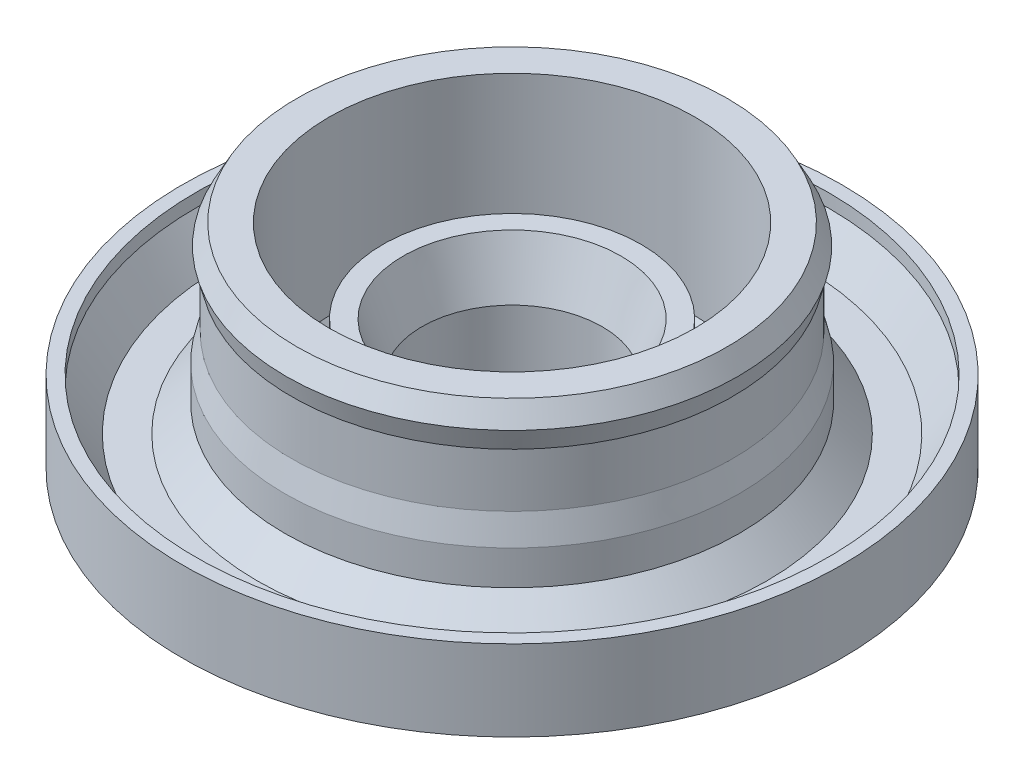
SolidWorks part; units mm, degrees
ref_plane "Front Plane" through (0, 0, 0) normal (0, 0, 1) x (1, 0, 0)
ref_plane "Top Plane" through (0, 0, 0) normal (0, 1, 0) x (1, 0, 0)
ref_plane "Right Plane" through (0, 0, 0) normal (1, 0, 0) x (0, 0, -1)
sketch "Sketch1" plane through (0, 0, 0) normal (0, 0, 1) x (1, 0, 0)
  line L0 (0, 0) -> (0, 11.7229) construction
  line L1 (-12.25, 7.1) -> (-4.45, 7.1)
  line L2 (-4.45, 7.1) -> (-4.45, 0)
  line L3 (-4.45, 0) -> (-6, 0)
  line L4 (-6, 0) -> (-6, 4.1)
  line L5 (-6, 4.1) -> (-12.25, 4.1)
  line L6 (-12.25, 4.1) -> (-12.25, 7.1)
  dimension "D1" = 6
  dimension "D2" = 4.45
  dimension "D3" = 4.1
  dimension "D4" = 3
  dimension "D5" = 12.25
revolve "Revolve1" add sketch "Sketch1" angle 360 about L0
sketch "Sketch6" plane through (0, 0, 0) normal (0, 0, 1) x (1, 0, 0)
  line L0 (-11.75, 7.1) -> (-11.75, 6.6)
  line L1 (12.25, 7.1) -> (-12.25, 7.1) construction
  line L2 (-11.75, 6.6) -> (-10.7697, 5.2)
  line L3 (-10.7697, 5.2) -> (-6.8, 5.2)
  line L4 (-6.8, 5.2) -> (-6.8, 4.5)
  line L5 (-6.8, 4.5) -> (0, 4.5)
  line L6 (0, 4.5) -> (0, 7.1)
  line L7 (4.45, 7.1) -> (-4.45, 7.1) construction
  line L8 (0, 7.1) -> (0, 9.85)
  line L9 (0, 9.85) -> (-11.75, 9.85)
  line L10 (-11.75, 9.85) -> (-11.75, 7.1)
  dimension "D1" = 0.5
  dimension "D2" = 0.5
  dimension "D3" = 1.1
  dimension "D4" = 0.7
  dimension "D5" = 6.8
  dimension "D6" = 35
  dimension "D7" = 3.9697
revolve "Cut-Revolve2" cut sketch "Sketch6" angle 360 about L6
ref_plane "Plane1" through (0, 5.2, 0) normal (0, 1, 0) x (1, 0, 0)
sketch "Sketch7" plane through (0, 0, 0) normal (0, 0, 1) x (1, 0, 0)
  line L0 (-4.8, 8.9) -> (-4.8, 3.7444)
  line L1 (-4.8, 3.7444) -> (-3.35, 3.7444)
  line L2 (-3.35, 3.7444) -> (-3.35, 6.9768)
  line L3 (-3.35, 6.9768) -> (-4.05, 8.9)
  line L4 (-4.05, 8.9) -> (-4.8, 8.9)
  line L5 (0, 0) -> (0, 11.3541) construction
  line L7 (6.8, 4.5) -> (-6.8, 4.5) construction
  dimension "D1" = 0.75
  dimension "D2" = 4.8
  dimension "D3" = 3.35
  dimension "D4" = 20
  dimension "D5" = 4.4
revolve "Revolve2" add sketch "Sketch7" angle 360 about L5
sketch "Sketch8" plane through (0, 3.7444, 0) normal (0, -1, 0) x (1, 0, 0)
  circle A0 centre (0, 0) radius 3.85
  circle A1 centre (0, 0) radius 3.35
  dimension "D1" = 7.7
extrude "Boss-Extrude1" add sketch "Sketch8" along normal blind 2.1
sketch "Sketch9" plane through (0, 0, 0) normal (0, 0, 1) x (1, 0, 0)
  line L0 (0, 0) -> (0, 16.743) construction
  line L1 (-6.7998, 12) -> (-6.7998, 5.2)
  line L2 (-6.7998, 5.2) -> (-9.4698, 5.2)
  line L3 (-9.4698, 5.2) -> (-8.45, 6.2198)
  line L4 (-8.45, 6.2198) -> (-8.45, 7.5)
  line L9 (-7.9998, 12) -> (-6.7998, 12)
  line L10 (13.475, 5.2) -> (-13.475, 5.2) construction
  line L13 (-8.2, 10.5) -> (-8.2, 8.5)
  line L14 (-8.2, 8.5) -> (-8.45, 7.5)
  line L15 (-7.9998, 12) -> (-8.401, 11.25)
  line L16 (-8.401, 11.25) -> (-8.2, 10.5)
  point P5 (-8.2, 9.5)
  dimension "D1" = 6.7998
  dimension "D2" = 8.45
  dimension "D3" = 45
  dimension "D4" = 8.2
  dimension "D5" = 12
  dimension "D6" = 15
  dimension "D7" = 1.5
  dimension "D8" = 1.2
  dimension "D9" = 2
  dimension "D10" = 1
  dimension "D11" = 2.67
  dimension "D12" = 0.75
revolve "Revolve3" add sketch "Sketch9" angle 360 about L0
sketch "Sketch11" plane through (0, 0, 0) normal (0, 0, 1) x (1, 0, 0)
  line L0 (0, 0) -> (0, 14.9707) construction
  line L3 (-6.7998, 5.6) -> (-6, 4.5)
  line L15 (-6, 4.3089) -> (-7.1398, 4.3089)
  line L22 (-6.7998, 5.6) -> (-7.1398, 5.6)
  line L23 (-7.1398, 5.6) -> (-7.1398, 4.3089)
  line L24 (-12.25, 4.1) -> (12.25, 4.1) construction
  line L25 (6.8, 4.5) -> (-6.8, 4.5) construction
  line L26 (-6, 4.5) -> (-6, 4.3089)
  dimension "D1" = 1.5
  dimension "D2" = 6
revolve "Revolve4" add sketch "Sketch11" angle 360 about L0
fillet "Fillet2" radius 0.5 1 edges at (0, 0, -6)
fillet "Fillet3" radius 0.2 1 edges at (0, 1.6444, -3.85)
equation "\"2.1.00mm\"=10"
